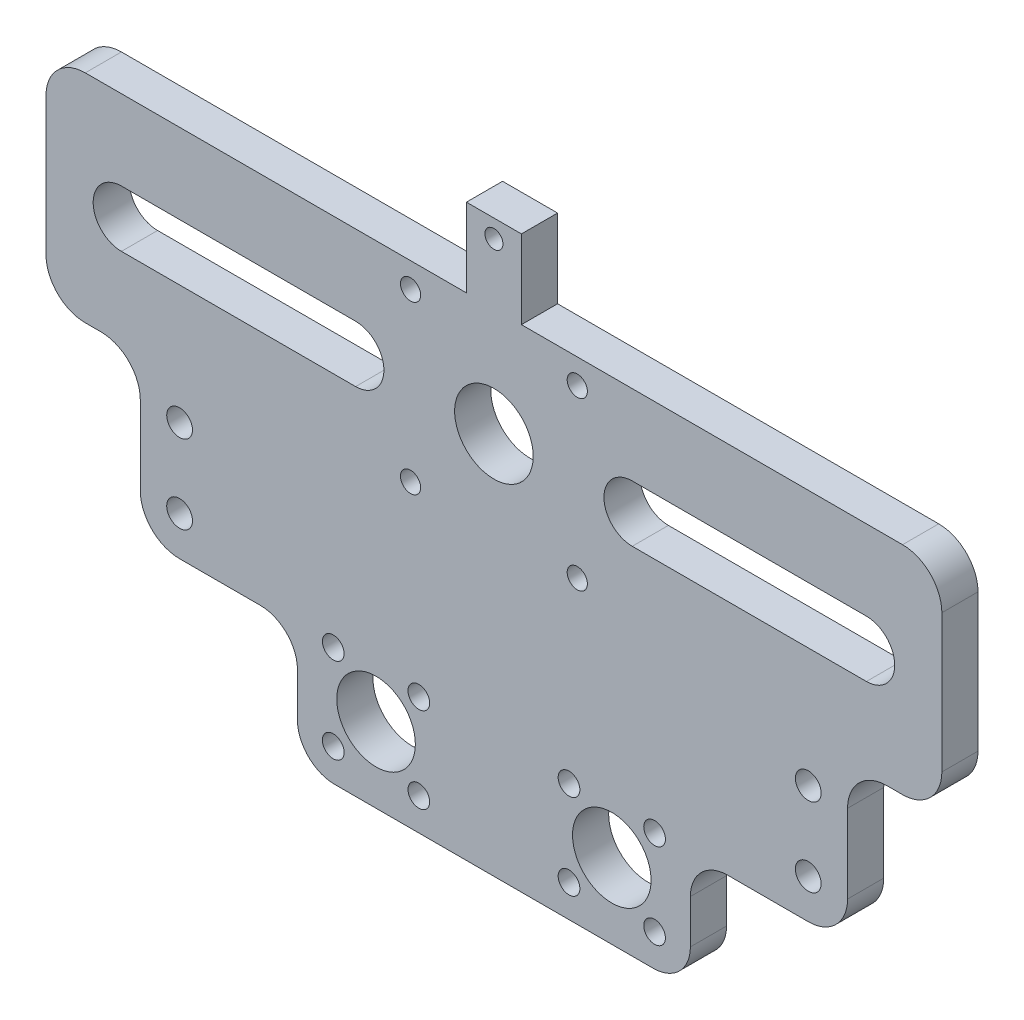
SolidWorks part; units mm, degrees
ref_plane "Front Plane" through (0, 0, 0) normal (0, 0, 1) x (1, 0, 0)
ref_plane "Top Plane" through (0, 0, 0) normal (0, 1, 0) x (1, 0, 0)
ref_plane "Right Plane" through (0, 0, 0) normal (1, 0, 0) x (0, 0, -1)
sketch "Sketch1" plane through (0, 0, 0) normal (0, 0, 1) x (1, 0, 0)
  line L0 (22.352, 0) -> (60.198, 0) construction
  line L1 (22.352, 4.572) -> (60.198, 4.572)
  line L2 (22.352, -4.572) -> (60.198, -4.572)
  line L3 (17.78, 5.5995) -> (17.78, -9.2529) construction
  line L4 (64.77, 5.5995) -> (64.77, -6.9009) construction
  line L5 (0, 17.4942) -> (0, -17.4943) construction
  line L6 (-22.352, 0) -> (-60.198, 0) construction
  line L7 (-22.352, 4.572) -> (-60.198, 4.572)
  line L8 (-22.352, -4.572) -> (-60.198, -4.572)
  line L12 (-72.39, 17.4942) -> (72.39, 17.4942)
  line L13 (-72.39, 17.4942) -> (-72.39, -17.4943)
  line L14 (-72.39, -17.4943) -> (72.39, -17.4943)
  line L15 (72.39, 17.4942) -> (72.39, -17.4943)
  line L16 (72.39, -17.4943) -> (-72.39, 17.4942) construction
  line L17 (72.39, 17.4942) -> (-72.39, -17.4943) construction
  arc A0 (22.352, 4.572) -> (22.352, -4.572) centre (22.352, 0) ccw
  arc A2 (60.198, -4.572) -> (60.198, 4.572) centre (60.198, 0) ccw
  arc A3 (-22.352, 4.572) -> (-22.352, -4.572) centre (-22.352, 0) cw
  arc A4 (-60.198, -4.572) -> (-60.198, 4.572) centre (-60.198, 0) cw
  point P2 (41.275, 0)
  point P9 (17.78, 0)
  point P12 (64.77, 0)
  point P17 (-41.275, 0)
  dimension "D1" = 17.78
  dimension "D2" = 46.99
  dimension "D3" = 34.9885
  dimension "D4" = 144.78
  dimension "D5" = 9.144
extrude "Boss-Extrude1" add sketch "Sketch1" along normal mid plane 5.842
sketch "Sketch2" plane through (0, 0, 2.921) normal (0, 0, 1) x (1, 0, 0)
  line L0 (0, -17.4943) -> (0, 17.4943) construction
  line L1 (-72.39, -17.4943) -> (72.39, -17.4943) construction
  line L2 (72.39, 17.4942) -> (-72.39, 17.4942) construction
  line L3 (13.4704, -13.4704) -> (-13.4704, 13.4704) construction
  line L4 (13.4704, -13.4704) -> (-13.4704, -13.4704) construction
  line L5 (13.4704, -13.4704) -> (13.4704, 13.4704) construction
  line L6 (13.4704, 13.4704) -> (-13.4704, 13.4704) construction
  line L7 (-13.4704, -13.4704) -> (-13.4704, 13.4704) construction
  circle A0 centre (0, 0) radius 6.35
  circle A1 centre (13.4704, -13.4704) radius 1.632
  circle A2 centre (-13.4704, -13.4704) radius 1.6319
  circle A3 centre (-13.4704, 13.4704) radius 1.6319
  circle A4 centre (13.4704, 13.4704) radius 1.632
  dimension "D1" = 12.7
  dimension "D2" = 3.2639
  dimension "D3" = 38.1
extrude "Cut-Extrude1" cut sketch "Sketch2" against normal through all
fillet "Fillet1" radius 6.35 4 edges at (-72.39, -17.4943, 0) (-72.39, 17.4942, 0) (72.39, -17.4943, 0) (72.39, 17.4942, 0)
sketch "Sketch3" plane through (0, 0, 2.921) normal (0, 0, 1) x (1, 0, 0)
  line L0 (-66.04, -17.4943) -> (66.04, -17.4943) construction
  line L1 (-57.15, -17.4943) -> (57.15, -17.4943)
  line L2 (-57.15, -17.4943) -> (-57.15, -42.8943)
  line L3 (-57.15, -42.8943) -> (57.15, -42.8943)
  line L4 (57.15, -17.4943) -> (57.15, -42.8943)
  line L5 (0, -42.8943) -> (0, -17.4943) construction
  dimension "D1" = 114.3
  dimension "D2" = 25.4
extrude "Boss-Extrude2" add sketch "Sketch3" against normal blind 5.842
sketch "Sketch4" plane through (0, 0, -2.921) normal (0, 0, -1) x (-1, 0, 0)
  line L2 (0, 17.4942) -> (0, -42.8943) construction
  line L6 (-66.04, 17.4942) -> (66.04, 17.4942) construction
  line L8 (57.15, -42.8943) -> (-57.15, -42.8943) construction
  line L10 (-31.75, -61.9443) -> (31.75, -61.9443)
  line L11 (-31.75, -61.9443) -> (-31.75, -42.8943)
  line L12 (-31.75, -42.8943) -> (31.75, -42.8942)
  line L13 (31.75, -61.9443) -> (31.75, -42.8942)
  line L14 (-31.75, -61.9443) -> (31.75, -42.8942) construction
  line L15 (-31.75, -42.8943) -> (31.75, -61.9443) construction
  point P8 (0, -52.4193)
  dimension "D1" = 9.525
  dimension "D2" = 63.5
fillet "Fillet2" radius 6.35 4 edges at (-57.15, -17.4943, 0) (-57.15, -42.8943, 0) (57.15, -42.8943, 0) (57.15, -17.4943, 0)
sketch "Sketch5" plane through (0, 0, -2.921) normal (0, 0, -1) x (-1, 0, 0)
  circle A0 centre (-50.8, -36.5443) radius 2.0828
  circle A1 centre (50.8, -36.5443) radius 2.0828
  arc A2 (-57.15, -36.5443) -> (-50.8, -42.8943) centre (-50.8, -36.5443) ccw construction
  arc A3 (50.8, -42.8943) -> (57.15, -36.5443) centre (50.8, -36.5443) ccw construction
  circle A4 centre (50.8, -23.8443) radius 2.0828
  circle A5 centre (-50.8, -23.8443) radius 2.0828
  dimension "D1" = 4.1656
  dimension "D2" = 12.7
extrude "Cut-Extrude3" cut sketch "Sketch5" against normal through all
sketch "Sketch6" plane through (0, 0, -2.921) normal (0, 0, -1) x (-1, 0, 0)
  line L0 (-66.04, 17.4942) -> (66.04, 17.4942) construction
  line L1 (-4.445, 17.4942) -> (4.445, 17.4942)
  line L2 (-4.445, 17.4942) -> (-4.445, 30.1942)
  line L3 (-4.445, 30.1942) -> (4.445, 30.1942)
  line L4 (4.445, 17.4942) -> (4.445, 30.1942)
  line L5 (-4.445, 27.2732) -> (4.445, 27.2732) construction
  circle A0 centre (0, 27.2732) radius 1.4605
  point P6 (0, 17.4942)
  dimension "D3" = 2.921
  dimension "D1" = 2.921
  dimension "D2" = 8.89
  dimension "D4" = 12.7
extrude "Boss-Extrude3" add sketch "Sketch6" against normal blind 5.842
extrude "Boss-Extrude4" add sketch "Sketch4" against normal up to surface (5.842 mm away) up to face at (48.7172, -23.8443, 2.921)
ref_plane "Plane1" through (0, 0, 0) normal (-1, 0, 0) x (0, 0, 1)
sketch "Sketch7" plane through (0, 0, -2.921) normal (0, 0, -1) x (-1, 0, 0)
  line L0 (0, 30.1943) -> (0, -61.9443) construction
  line L1 (4.445, 30.1942) -> (-4.445, 30.1942) construction
  line L2 (-31.75, -61.9443) -> (31.75, -61.9443) construction
  line L3 (-31.75, -42.8943) -> (-50.8, -42.8943) construction
  line L7 (-25.9648, -56.7238) -> (-12.1352, -56.7238) construction
  line L8 (-25.9648, -56.7238) -> (-25.9648, -42.8943) construction
  line L9 (-25.9648, -42.8943) -> (-12.1352, -42.8943) construction
  line L10 (-12.1352, -56.7238) -> (-12.1352, -42.8943) construction
  line L11 (-25.9648, -56.7238) -> (-12.1352, -42.8943) construction
  line L12 (-25.9648, -42.8943) -> (-12.1352, -56.7238) construction
  circle A0 centre (-19.05, -49.809) radius 6.35
  point P12 (-19.05, -49.809)
  dimension "D3" = 12.7
  dimension "D1" = 19.558
  dimension "D2" = 19.05
extrude "Cut-Extrude4" cut sketch "Sketch7" against normal through all
hole_wizard "#6 Clearance Hole1" positions "Sketch8" profile "Sketch9" hole size "#6" standard "ANSI Inch"
sketch "Sketch8" plane through (0, 0, -2.921) normal (0, 0, -1) x (-1, 0, 0)
  line L1 (-25.9648, -56.7238) -> (-12.1352, -56.7238) construction
  line L2 (-25.9648, -56.7238) -> (-25.9648, -42.8942) construction
  line L3 (-25.9648, -42.8942) -> (-12.1352, -42.8942) construction
  line L4 (-12.1352, -56.7238) -> (-12.1352, -42.8942) construction
  line L5 (-25.9648, -56.7238) -> (-12.1352, -42.8942) construction
  line L6 (-25.9648, -42.8942) -> (-12.1352, -56.7238) construction
  circle A1 centre (-19.05, -49.809) radius 6.35 construction
  circle A2 centre (-19.05, -49.809) radius 6.35 construction
  point P70 (-25.9648, -42.8942)
  dimension "D1" = 19.558
sketch "Sketch9" plane through (25.9648, -42.8942, -2.921) normal (1, 0, 0) x (0, 1, 0)
  line L0 (0, 0) -> (0, 10.4511)
  line L1 (0, 10.4511) -> (1.7526, 9.398)
  line L2 (1.7526, 9.398) -> (1.7526, 0)
  line L5 (1.7526, 0) -> (0, 0)
  line L10 (0, 10.4511) -> (-1.7526, 9.398) construction
  line L11 (0, -6.35) -> (0, 107.95) construction
  dimension "Hole Dia." = 3.5052
  dimension "Hole Depth" = 9.398
  dimension "Drill Angle" = 118
pattern_circular "CirPattern1" count 4 over 360 about axis through (19.05, -49.809, 0) along (0, 0, 1) of "#6 Clearance Hole1"
mirror "Mirror1" about plane through (0, 0, 0) normal (-1, 0, 0) of "CirPattern1", "#6 Clearance Hole1", "Cut-Extrude4"
fillet "Fillet3" radius 6 4 edges at (31.75, -42.8943, 0) (31.75, -61.9443, 0) (-31.75, -61.9443, 0) (-31.75, -42.8942, 0)
